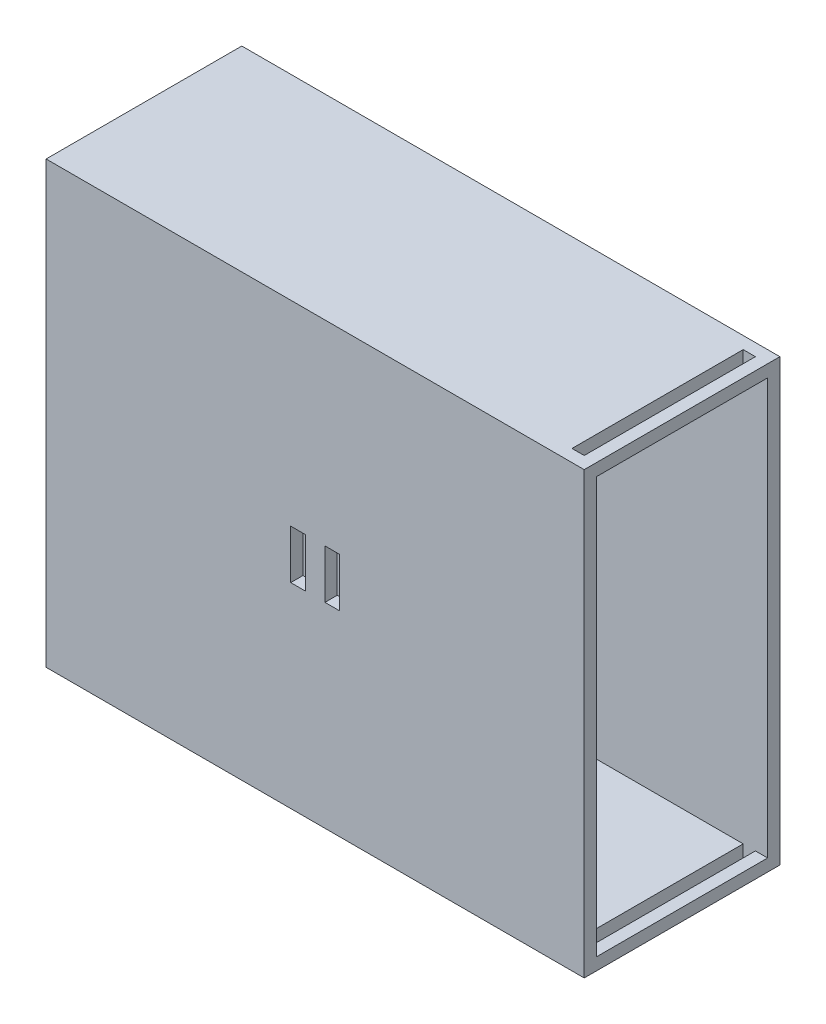
SolidWorks part; units mm, degrees
material "Custom Plastic"
ref_plane "Front Plane" through (0, 0, 0) normal (0, 0, 1) x (1, 0, 0)
ref_plane "Top Plane" through (0, 0, 0) normal (0, 1, 0) x (1, 0, 0)
ref_plane "Right Plane" through (0, 0, 0) normal (1, 0, 0) x (0, 0, -1)
sketch "Main Body" plane through (0, 0, 0) normal (0, 0, 1) x (1, 0, 0)
  line L4 (-79.6784, 0) -> (199.7216, 0)
  line L5 (199.7216, 0) -> (199.7216, -228.6)
  line L6 (199.7216, -228.6) -> (-79.6784, -228.6)
  line L7 (-79.6784, -228.6) -> (-79.6784, 0)
  dimension "D1" = 279.4
  dimension "D2" = 228.6
extrude "Main Body Extrude" add sketch "Main Body" along normal blind 101.6 contours L7 L6 L5 L4
ref_plane "Plane1" through (199.7216, 0, 0) normal (1, 0, 0) x (0, 0, -1)
sketch "Sketch2" plane through (199.7216, 0, 0) normal (1, 0, 0) x (0, 0, -1)
  line L0 (-95.25, -6.35) -> (-6.35, -6.35)
  line L1 (-6.35, -6.35) -> (-6.35, -222.25)
  line L2 (-6.35, -222.25) -> (-95.25, -222.25)
  line L3 (-95.25, -222.25) -> (-95.25, -6.35)
  line L4 (0, 0) -> (0, -228.6) construction
  line L5 (-101.6, -228.6) -> (0, -228.6) construction
  dimension "D1" = 88.9
  dimension "D2" = 215.9
  dimension "D3" = 6.35
  dimension "D4" = 6.35
extrude "Main Body Hollow Extrude Cut" cut sketch "Sketch2" against normal blind 273.05 contours L3 L2 L1 L0
ref_plane "Plane2" through (0, 0, 0) normal (0, 1, 0) x (1, 0, 0)
sketch "Sketch3" plane through (0, 0, 0) normal (0, 1, 0) x (1, 0, 0)
  line L0 (187.0216, -6.35) -> (187.0216, -95.25)
  line L1 (187.0216, -95.25) -> (193.3716, -95.25)
  line L2 (193.3716, -95.25) -> (193.3716, -6.35)
  line L3 (193.3716, -6.35) -> (187.0216, -6.35)
  line L4 (199.7216, -101.6) -> (199.7216, 0) construction
  line L5 (-79.6784, 0) -> (199.7216, 0) construction
  dimension "D1" = 6.35
  dimension "D2" = 6.35
  dimension "D3" = 6.35
  dimension "D4" = 88.9
extrude "Sliding Door Extrude Cut" cut sketch "Sketch3" against normal blind 273.05
ref_plane "Plane3" through (0, 0, 101.6) normal (0, 0, 1) x (1, 0, 0)
sketch "Sketch4" plane through (0, 0, 101.6) normal (0, 0, 1) x (1, 0, 0)
  line L0 (47.3216, -101.6) -> (47.3216, -127)
  line L1 (47.3216, -127) -> (54.9416, -127)
  line L2 (54.9416, -127) -> (54.9416, -101.6)
  line L3 (54.9416, -101.6) -> (47.3216, -101.6)
  line L4 (65.1016, -101.6) -> (72.7216, -101.6)
  line L5 (72.7216, -101.6) -> (72.7216, -127)
  line L6 (72.7216, -127) -> (65.1016, -127)
  line L7 (65.1016, -127) -> (65.1016, -101.6)
  line L8 (199.7216, 0) -> (199.7216, -228.6) construction
  line L9 (-79.6784, -228.6) -> (-79.6784, 0) construction
  line L12 (199.7216, -228.6) -> (-79.6784, -228.6) construction
  dimension "D1" = 127
  dimension "D2" = 127
  dimension "D3" = 7.62
  dimension "D4" = 25.4
  dimension "D5" = 101.6
extrude "Cut-Extrude3" cut sketch "Sketch4" against normal blind 25.4
